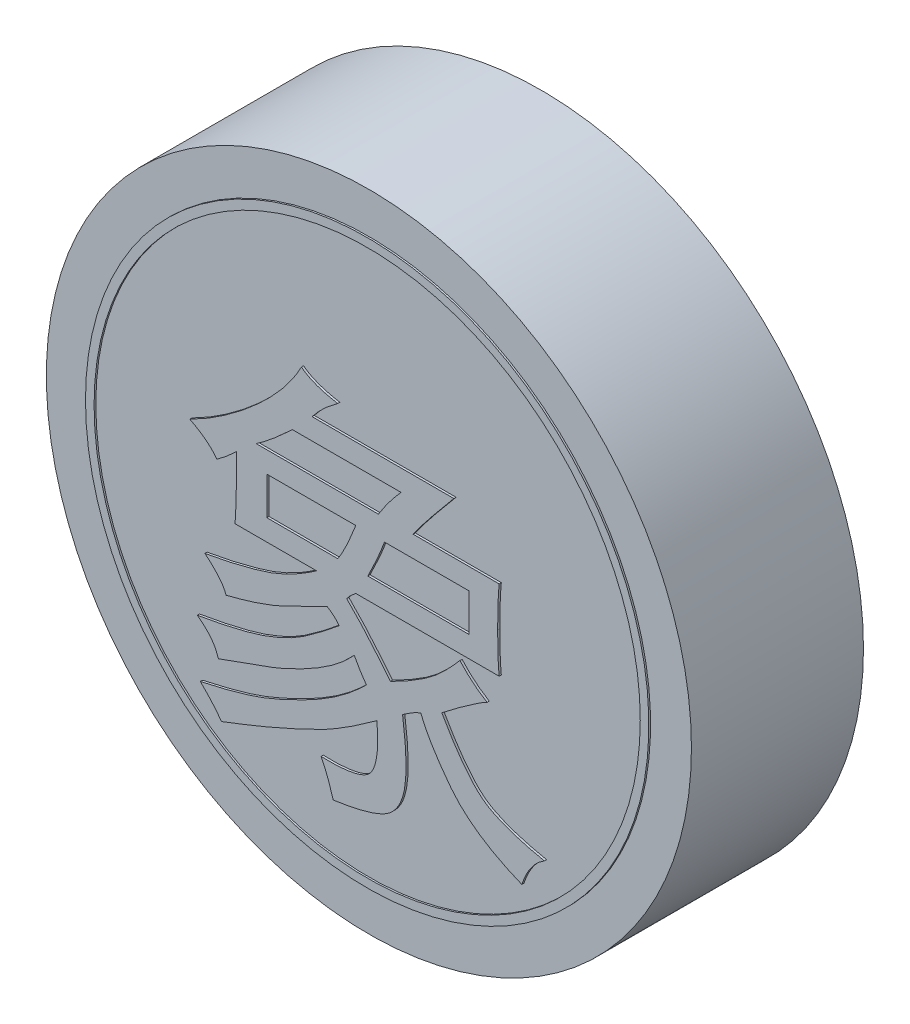
SolidWorks part; units mm, degrees
ref_plane "前视基准面" through (0, 0, 0) normal (0, 0, 1) x (1, 0, 0)
ref_plane "上视基准面" through (0, 0, 0) normal (0, 1, 0) x (1, 0, 0)
ref_plane "右视基准面" through (0, 0, 0) normal (1, 0, 0) x (0, 0, -1)
other "Configuration Table"
sketch "草图1" plane through (0, 0, 0) normal (0, 0, 1) x (1, 0, 0)
  circle A0 centre (0, 0) radius 15
  dimension "D1" = 30
extrude "Diameter30_Height8" add sketch "草图1" against normal blind 8
sketch "草图2" plane through (0, 0, 0) normal (0, 0, 1) x (1, 0, 0)
  text T0 "象" font "SimHei" height 12
extrude "Character_象" add sketch "草图2" along normal blind 0.1
sketch "草图3" plane through (0, 0, 0) normal (0, 0, 1) x (1, 0, 0)
  circle A0 centre (0, 0) radius 13.1
  circle A1 centre (0, 0) radius 12.7
extrude "Ink_ring" add sketch "草图3" along normal blind 0.08
